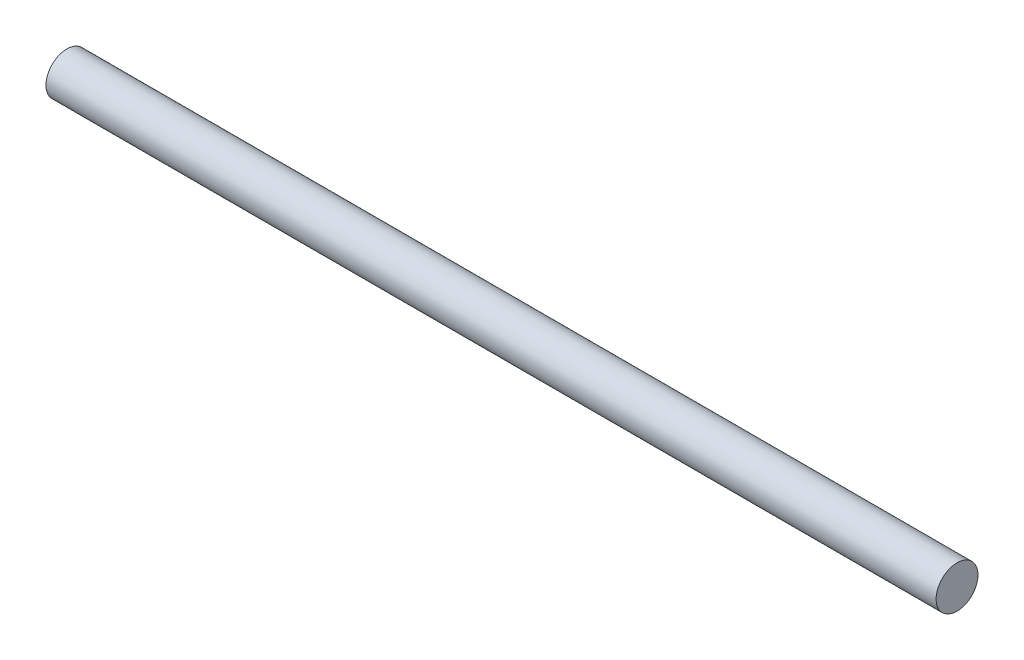
SolidWorks part; units mm, degrees
ref_plane "Plan de face" through (0, 0, 0) normal (0, 0, 1) x (1, 0, 0)
ref_plane "Plan de dessus" through (0, 0, 0) normal (0, 1, 0) x (1, 0, 0)
ref_plane "Plan de droite" through (0, 0, 0) normal (1, 0, 0) x (0, 0, -1)
sketch "Esquisse1" plane through (0, 0, 0) normal (1, 0, 0) x (0, 0, -1)
  circle A0 centre (0, 0) radius 10.125
  dimension "D1" = 20.25
extrude "Boss.-Extru.1" add sketch "Esquisse1" along normal blind 430
